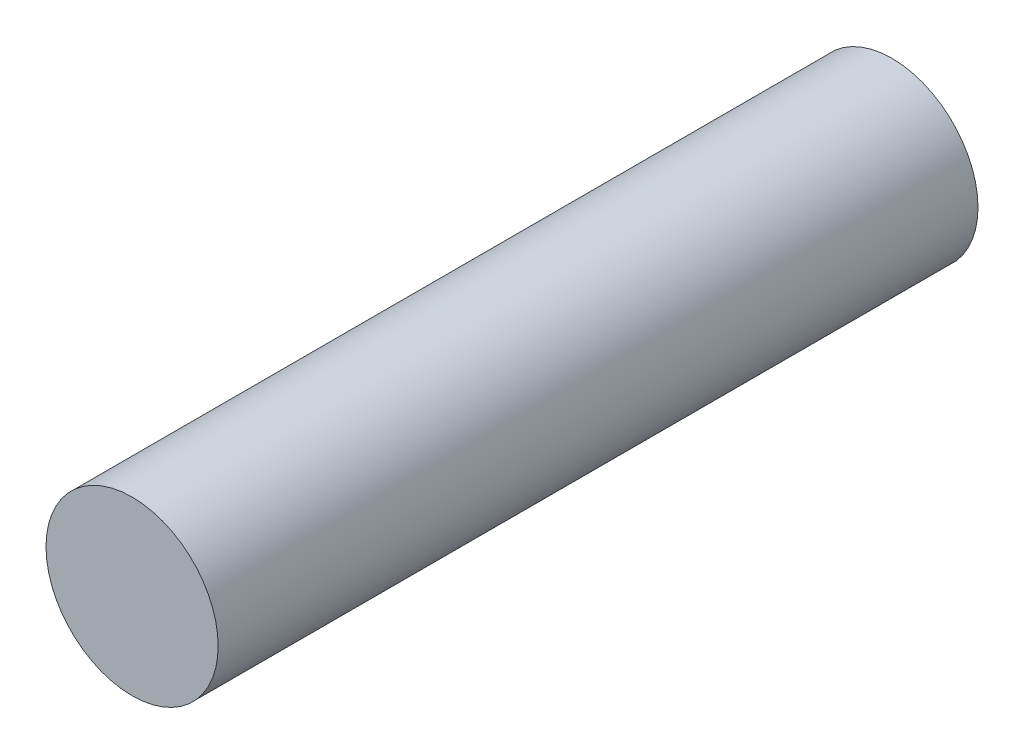
SolidWorks part; units mm, degrees
ref_plane "Front Plane" through (0, 0, 0) normal (0, 0, 1) x (1, 0, 0)
ref_plane "Top Plane" through (0, 0, 0) normal (0, 1, 0) x (1, 0, 0)
ref_plane "Right Plane" through (0, 0, 0) normal (1, 0, 0) x (0, 0, -1)
sketch "Sketch1" plane through (0, 0, 0) normal (0, 0, 1) x (1, 0, 0)
  circle A0 centre (0, 0) radius 1.0795
  dimension "D1" = 2.159
extrude "Boss-Extrude1" add sketch "Sketch1" along normal blind 9.5301
equation "\"D1@Sketch1\"=\"imu_hole_diameter\""
equation "\"D1@Boss-Extrude1\"=\"standoff_small\""
equation "\"material_width\" = 0.1795"
equation "\"max32_width\" = 2.1"
equation "\"max32_length\" = 4.0"
equation "\"max32_hole_diameter\" = 0.12"
equation "\"max32_dist2hole_width\" = 0.1"
equation "\"max32_dist2hole1_length\" = 0.6"
equation "\"max32_dist2hole2_length\" = 3.8"
equation "\"head_height\" = 2.0"
equation "\"neck_height\" = \"max32_width\""
equation "\"washer_height\" = 0.1"
equation "\"wall_length\" = 3.5"
equation "\"wall_height\" = 1.5"
equation "\"extra_space\" = 0.25"
equation "\"arc_radius\" = \"wall_length\" + \"washer_height\" + \"neck_height\" + (\"head_height\"/2)"
equation "\"arc_wall_height\" = \"arc_radius\" + \"wall_length\" + \"extra_space\""
equation "\"foot_length\" = 1.0"
equation "\"peg_diameter\" = 0.2475"
equation "\"barring_diameter\" = 0.8657"
equation "\"imu_space\" = 0.8"
equation "\"encoder_height\" = 0.8587"
equation "\"encoder_sub_height\" = 0.3827"
equation "\"encoder_length\" = 1.1043"
equation "\"encoder_sub_length\" = 0.5886"
equation "\"encoder_width\" = 0.8669"
equation "\"standoff_small\" = 0.3752"
equation "\"imu_hole_diameter\" = 0.085"
